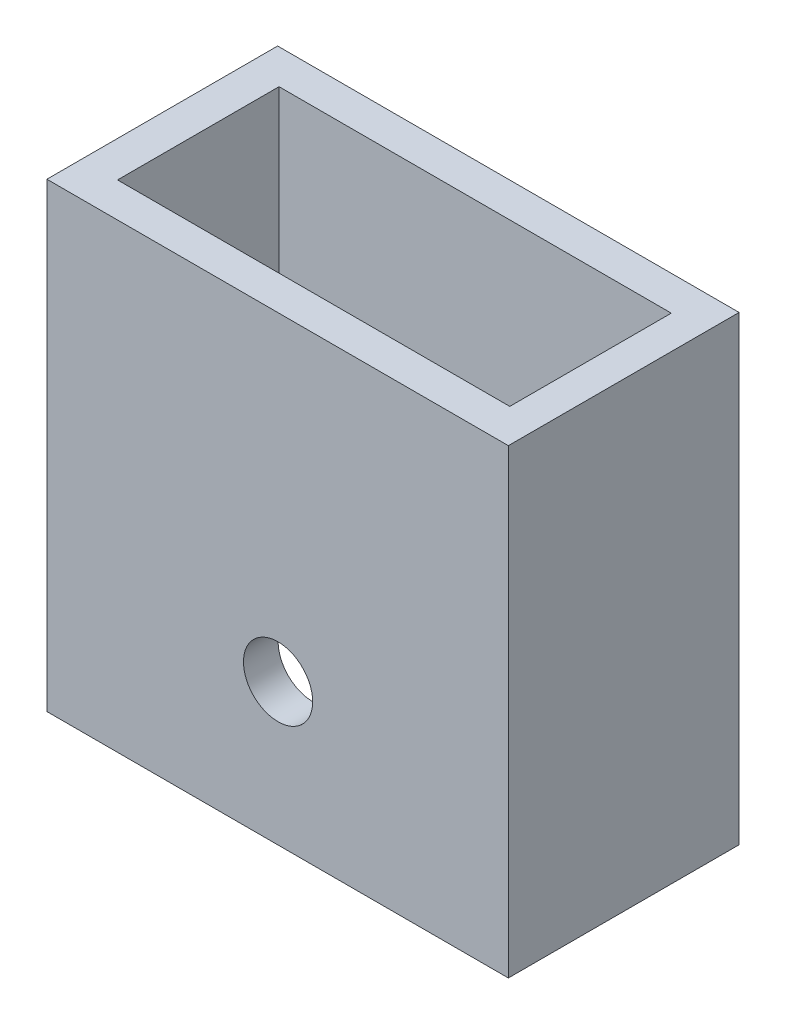
SolidWorks part; units mm, degrees
material "PETG"
ref_plane "Front Plane" through (0, 0, 0) normal (0, 0, 1) x (1, 0, 0)
ref_plane "Top Plane" through (0, 0, 0) normal (0, 1, 0) x (1, 0, 0)
ref_plane "Right Plane" through (0, 0, 0) normal (1, 0, 0) x (0, 0, -1)
sketch "Sketch1" plane through (0, 0, 0) normal (0, 0, 1) x (1, 0, 0)
  line L1 (-74.6877, -25.5242) -> (-34.6877, -25.5242)
  line L2 (-74.6877, -25.5242) -> (-74.6877, -65.4861)
  line L3 (-74.6877, -65.4861) -> (-34.6877, -65.4861)
  line L4 (-34.6877, -25.5242) -> (-34.6877, -65.4861)
extrude "Boss-Extrude1" add sketch "Sketch1" along normal blind 20 contours L1 L4 L3 L2
sketch "Sketch2" plane through (0, 0, 0) normal (0, 1, 0) x (1, 0, 0)
  line L1 (-71.5733, -2.9928) -> (-37.5733, -2.9928)
  line L2 (-71.5733, -2.9928) -> (-71.5733, -16.9928)
  line L3 (-71.5733, -16.9928) -> (-37.5733, -16.9928)
  line L4 (-37.5733, -2.9928) -> (-37.5733, -16.9928)
extrude "Cut-Extrude8" cut sketch "Sketch2" against normal blind 200 contours L1 L4 L3 L2
sketch "Sketch11" plane through (0, 0, 20) normal (0, 0, 1) x (1, 0, 0)
  circle A0 centre (-54.6504, -53.2304) radius 3
extrude "Cut-Extrude9" cut sketch "Sketch11" against normal blind 200 contours A0
